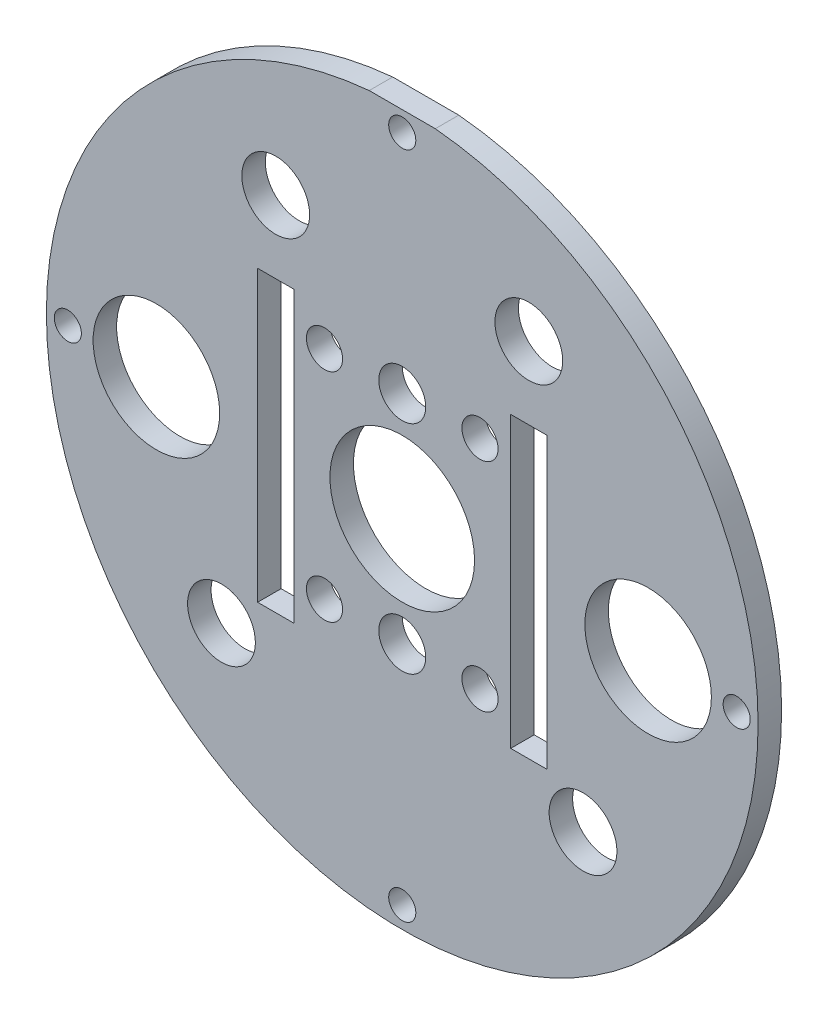
SolidWorks part; units mm, degrees
ref_plane "前视基准面" through (0, 0, 0) normal (0, 0, 1) x (1, 0, 0)
ref_plane "上视基准面" through (0, 0, 0) normal (0, 1, 0) x (1, 0, 0)
ref_plane "右视基准面" through (0, 0, 0) normal (1, 0, 0) x (0, 0, -1)
sketch "草图1" plane through (0, 0, 0) normal (0, 0, 1) x (1, 0, 0)
  circle A0 centre (0, 0) radius 50
  dimension "D1" = 100
extrude "凸台-拉伸1" add sketch "草图1" along normal blind 3.302
sketch "草图2" plane through (0, 0, 3.302) normal (0, 0, 1) x (1, 0, 0)
  line L0 (0, 0) -> (0, 69.5531) construction
  circle A0 centre (-17.78, 30.48) radius 4.7625
  circle A1 centre (-25.4, -25.4) radius 4.7625
  circle A2 centre (25.4, -25.4) radius 4.7625
  circle A3 centre (17.78, 30.48) radius 4.7625
  dimension "D1" = 9.525
  dimension "D2" = 9.525
  dimension "D3" = 17.78
  dimension "D4" = 9.525
  dimension "D5" = 25.4
  dimension "D6" = 25.4
  dimension "D7" = 30.48
extrude "切除-拉伸1" cut sketch "草图2" against normal through all
sketch "草图4" plane through (0, 0, 3.302) normal (0, 0, 1) x (1, 0, 0)
  circle A0 centre (0, 0) radius 10.16
  dimension "D1" = 20.32
extrude "切除-拉伸3" cut sketch "草图4" against normal through all
sketch "草图3" plane through (0, 0, 3.302) normal (0, 0, 1) x (1, 0, 0)
  line L0 (-4.6426, 49.784) -> (4.6426, 49.784)
  line L1 (4.6426, 49.784) -> (4.6426, 57.8305)
  line L2 (4.6426, 57.8305) -> (-4.6426, 57.8305)
  line L3 (-4.6426, 57.8305) -> (-4.6426, 49.784)
  circle A0 centre (0, 0) radius 50 construction
  dimension "D1" = 49.784
extrude "切除-拉伸2" cut sketch "草图3" against normal through all
sketch "草图6" plane through (0, 0, 3.302) normal (0, 0, 1) x (1, 0, 0)
  line L0 (0, 49.784) -> (0, -63.1689) construction
  line L1 (-4.6426, 49.784) -> (4.6426, 49.784) construction
  line L2 (-55.4747, 0) -> (58.1198, 0) construction
sketch "草图8" plane through (0, 0, 3.302) normal (0, 0, 1) x (1, 0, 0)
  line L0 (0, 49.784) -> (0, -63.1689) construction
  line L1 (15.24, 20.32) -> (20.32, 20.32)
  line L2 (15.24, 20.32) -> (15.24, -20.32)
  line L3 (15.24, -20.32) -> (20.32, -20.32)
  line L4 (20.32, 20.32) -> (20.32, -20.32)
  line L6 (-55.4747, 0) -> (58.1198, 0) construction
  line L7 (0, 0) -> (0, 55.0156) construction
  line L8 (-20.32, 20.32) -> (-20.32, -20.32)
  line L9 (-15.24, -20.32) -> (-20.32, -20.32)
  line L10 (-15.24, 20.32) -> (-15.24, -20.32)
  line L11 (-15.24, 20.32) -> (-20.32, 20.32)
  circle A0 centre (34.544, 0) radius 8.89
  circle A1 centre (-34.544, 0) radius 8.89
  dimension "D5" = 17.78
  dimension "D6" = 34.544
  dimension "D1" = 15.24
  dimension "D2" = 5.08
  dimension "D3" = 40.64
  dimension "D4" = 20.32
extrude "切除-拉伸4" cut sketch "草图8" against normal through all
sketch "草图9" plane through (0, 0, 3.302) normal (0, 0, 1) x (1, 0, 0)
  line L0 (0, 49.784) -> (0, -63.1689) construction
  line L2 (0, 38.6357) -> (0, -17.2565) construction
  line L3 (-24.6406, 0) -> (22.6594, 0) construction
  line L4 (-55.4747, 0) -> (58.1198, 0) construction
  circle A0 centre (-10.922, 15.24) radius 2.54
  circle A1 centre (10.922, 15.24) radius 2.54
  circle A2 centre (-10.922, -15.24) radius 2.54
  circle A3 centre (10.922, -15.24) radius 2.54
  circle A4 centre (0, 15.24) radius 3.302
  circle A5 centre (0, -15.24) radius 3.302
  dimension "D1" = 5.08
  dimension "D2" = 10.922
  dimension "D3" = 15.24
  dimension "D4" = 15.24
  dimension "D5" = 6.604
extrude "切除-拉伸5" cut sketch "草图9" against normal through all
sketch "草图10" plane through (0, 0, 3.302) normal (0, 0, 1) x (1, 0, 0)
  line L0 (-55.4747, 0) -> (58.1198, 0) construction
  circle A0 centre (0, 46.99) radius 1.905
  circle A1 centre (46.99, 0) radius 1.905
  circle A2 centre (0, -46.99) radius 1.905
  circle A3 centre (-46.99, 0) radius 1.905
  point P13 (0, 0)
  dimension "D1" = 3.81
  dimension "D2" = 46.99
  dimension "D3" = 4
extrude "切除-拉伸6" cut sketch "草图10" against normal through all
sketch "草图11" plane through (0, 0, 3.302) normal (0, 0, 1) x (1, 0, 0)
  circle A0 centre (0, 0) radius 50
